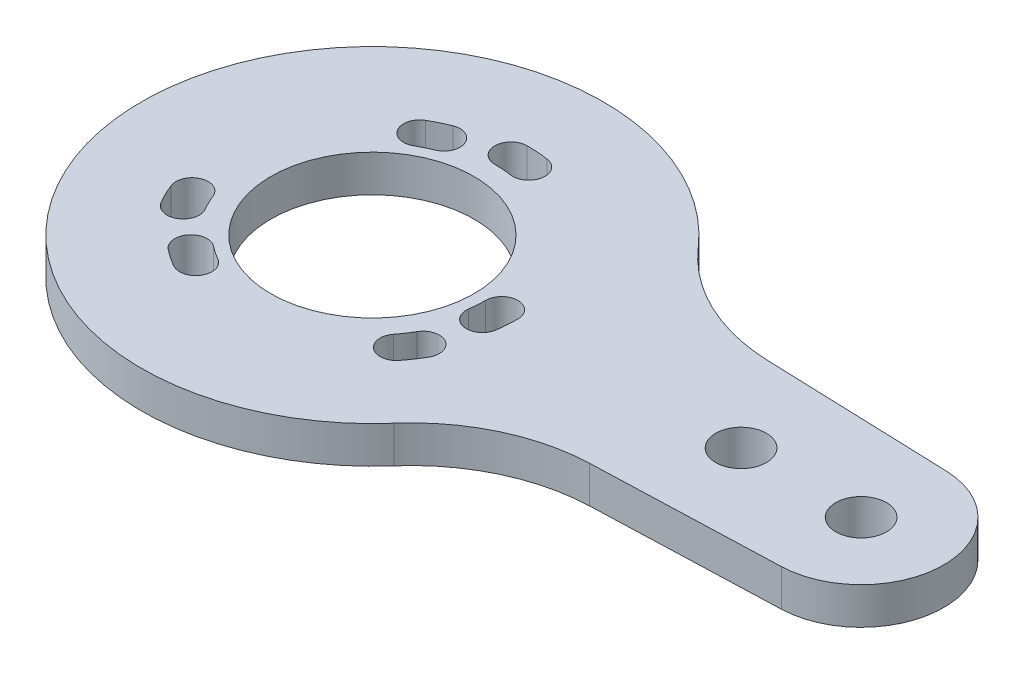
SolidWorks part; units mm, degrees
ref_plane "Front Plane" through (0, 0, 0) normal (0, 0, 1) x (1, 0, 0)
ref_plane "Top Plane" through (0, 0, 0) normal (0, 1, 0) x (1, 0, 0)
ref_plane "Right Plane" through (0, 0, 0) normal (1, 0, 0) x (0, 0, -1)
sketch "Sketch3" plane through (0, 0, 0) normal (0, 1, 0) x (1, 0, 0)
  line L0 (22.9129, 10) -> (53.2251, 8.9415)
  line L8 (53.2251, -8.9415) -> (22.9129, -10)
  line L10 (0, 0) -> (52.9129, 0) construction
  arc A0 (53.2251, 8.9415) -> (53.2251, -8.9415) centre (52.9129, 0) cw
  arc A5 (22.9129, 10) -> (22.9129, -10) centre (0, 0) ccw
  point P0 (0, 0)
  dimension "D1" = 50
  dimension "D3" = 2
  dimension "D4" = 2
  dimension "D5" = 20
  dimension "D7" = 30
extrude "Boss-Extrude1" add sketch "Sketch3" along normal blind 4
fillet "Fillet1" radius 20 2 edges at (22.9129, 2, 10) (22.9129, 2, -10)
sketch "Sketch1" plane through (103.3827, 0, 0) normal (0, 1, 0) x (1, 0, 0)
  line L1 (-103.3827, -42.2854) -> (-103.3827, 42.2854) construction
  circle A6 centre (-103.3827, 0) radius 11
  circle A9 centre (-63.4698, 0) radius 2.75
  circle A16 centre (-50.4698, 0) radius 2.75
  arc A17 (-50.1576, -8.9415) -> (-50.1576, 8.9415) centre (-50.4698, 0) ccw construction
  arc A18 (-111.2577, 13.6399) -> (-109.2827, 14.6031) centre (-103.3827, 0) cw
  arc A19 (-109.5077, 10.6088) -> (-107.9716, 11.358) centre (-103.3827, 0) cw
  arc A20 (-109.2827, 14.6031) -> (-107.9716, 11.358) centre (-108.6272, 12.9806) cw
  arc A21 (-111.2577, 13.6399) -> (-109.5077, 10.6088) centre (-110.3827, 12.1244) ccw
  arc A22 (-101.5386, 13.1211) -> (-103.3827, 13.25) centre (-103.3827, 0) ccw
  arc A23 (-103.3827, 16.75) -> (-101.0515, 16.587) centre (-103.3827, 0) cw
  arc A24 (-103.3827, 13.25) -> (-103.3827, 16.75) centre (-103.3827, 15) cw
  arc A25 (-101.5386, 13.1211) -> (-101.0515, 16.587) centre (-101.2951, 14.854) ccw
  arc A26 (-87.6327, 0) -> (-91.1327, 0) centre (-89.3827, 0) ccw
  arc A27 (-91.1327, 0) -> (-91.2519, -1.7049) centre (-103.3827, 0) cw
  arc A28 (-87.786, -2.192) -> (-91.2519, -1.7049) centre (-89.5189, -1.9484) cw
  arc A29 (-87.6327, 0) -> (-87.786, -2.192) centre (-103.3827, 0) cw
  arc A30 (-92.9415, -8.1575) -> (-90.1835, -10.3123) centre (-91.5625, -9.2349) ccw
  arc A31 (-88.8768, -8.375) -> (-90.1835, -10.3123) centre (-103.3827, 0) cw
  arc A32 (-91.9079, -6.625) -> (-88.8768, -8.375) centre (-90.3923, -7.5) cw
  arc A33 (-92.9415, -8.1575) -> (-91.9079, -6.625) centre (-103.3827, 0) ccw
  arc A34 (-111.2577, -13.6399) -> (-109.5077, -10.6088) centre (-110.3827, -12.1244) ccw
  arc A35 (-109.5077, -10.6088) -> (-110.9245, -9.6531) centre (-103.3827, 0) cw
  arc A36 (-113.0794, -12.4112) -> (-110.9245, -9.6531) centre (-112.002, -11.0322) cw
  arc A37 (-111.2577, -13.6399) -> (-113.0794, -12.4112) centre (-103.3827, 0) cw
  arc A38 (-115.6679, -4.9635) -> (-118.913, -6.2747) centre (-117.2904, -5.6191) ccw
  arc A39 (-117.8886, -8.375) -> (-118.913, -6.2747) centre (-103.3827, 0) cw
  arc A40 (-114.8575, -6.625) -> (-117.8886, -8.375) centre (-116.3731, -7.5) cw
  arc A41 (-115.6679, -4.9635) -> (-114.8575, -6.625) centre (-103.3827, 0) ccw
  point P13 (0, 0)
  point P43 (-103.3827, 0)
  dimension "D4" = 14
  dimension "D3" = 1.75
  dimension "D2" = 5.5
  dimension "D1" = 22
  dimension "D6" = 1.75
  dimension "D5" = 8
  dimension "D7" = 13
  dimension "D8" = 8
  dimension "D9" = 15
  dimension "D10" = 22
  dimension "D11" = 3
extrude "Cut-Extrude3" cut sketch "Sketch1" along normal through all
